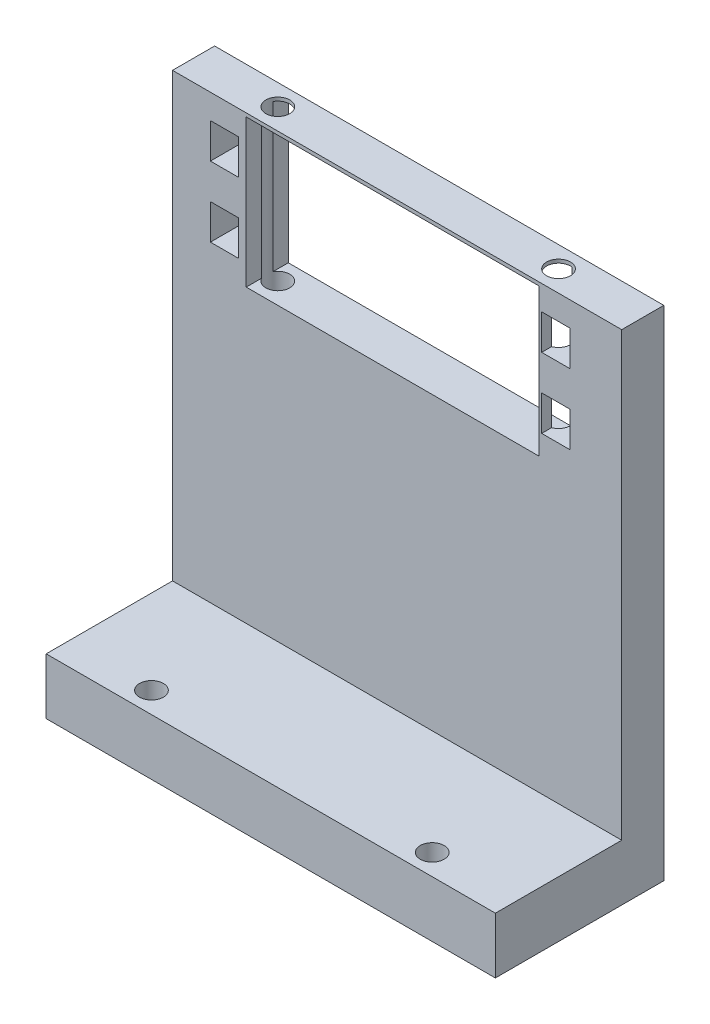
SolidWorks part; units mm, degrees
ref_plane "前视基准面" through (0, 0, 0) normal (0, 0, 1) x (1, 0, 0)
ref_plane "上视基准面" through (0, 0, 0) normal (0, 1, 0) x (1, 0, 0)
ref_plane "右视基准面" through (0, 0, 0) normal (1, 0, 0) x (0, 0, -1)
other "Configuration Table"
sketch "草图1" plane through (0, 0, 0) normal (0, 0, 1) x (1, 0, 0)
  line L1 (-21, 0) -> (43, 0)
  line L2 (-21, 0) -> (-21, 8)
  line L3 (-21, 8) -> (43, 8)
  line L4 (43, 0) -> (43, 8)
extrude "Servo_foot" add sketch "草图1" along normal blind 24
sketch "草图2" plane through (0, 0, 0) normal (0, 0, 1) x (1, 0, 0)
  line L1 (-21, 0) -> (43, 0)
  line L2 (-21, 0) -> (-21, 71)
  line L3 (-21, 71) -> (43, 71)
  line L4 (43, 0) -> (43, 71)
extrude "Servo_face_plate" add sketch "草图2" along normal blind 6
sketch "草图3" plane through (0, 0, 0) normal (0, 0, 1) x (1, 0, 0)
  line L1 (-10.5, 49.5) -> (31.2, 49.5)
  line L2 (-10.5, 49.5) -> (-10.5, 70.5)
  line L3 (-10.5, 70.5) -> (31.2, 70.5)
  line L4 (31.2, 49.5) -> (31.2, 70.5)
extrude "MG995_body_window_REFERENCE" cut sketch "草图3" against normal through all and the other way through all
sketch "草图4" plane through (0, 0, 0) normal (0, 0, 1) x (1, 0, 0)
  line L1 (-15.6, 52.5) -> (-11.6, 52.5)
  line L2 (-15.6, 52.5) -> (-15.6, 57.5)
  line L3 (-15.6, 57.5) -> (-11.6, 57.5)
  line L4 (-11.6, 52.5) -> (-11.6, 57.5)
  line L6 (-15.6, 62.5) -> (-11.6, 62.5)
  line L7 (-15.6, 62.5) -> (-15.6, 67.5)
  line L8 (-15.6, 67.5) -> (-11.6, 67.5)
  line L9 (-11.6, 62.5) -> (-11.6, 67.5)
  line L11 (31.6, 52.5) -> (35.6, 52.5)
  line L12 (31.6, 52.5) -> (31.6, 57.5)
  line L13 (31.6, 57.5) -> (35.6, 57.5)
  line L14 (35.6, 52.5) -> (35.6, 57.5)
  line L16 (31.6, 62.5) -> (35.6, 62.5)
  line L17 (31.6, 62.5) -> (31.6, 67.5)
  line L18 (31.6, 67.5) -> (35.6, 67.5)
  line L19 (35.6, 62.5) -> (35.6, 67.5)
extrude "MG995_47p2x10_reference_slots_VERIFY" cut sketch "草图4" against normal through all and the other way through all
sketch "草图5" plane through (0, 0, 0) normal (0, 1, 0) x (1, 0, 0)
  circle A0 centre (-9, -3) radius 1.7
  circle A1 centre (-9, -21) radius 1.7
  circle A2 centre (31, -3) radius 1.7
  circle A3 centre (31, -21) radius 1.7
extrude "Servo_foot_M3" cut sketch "草图5" against normal through all and the other way through all
